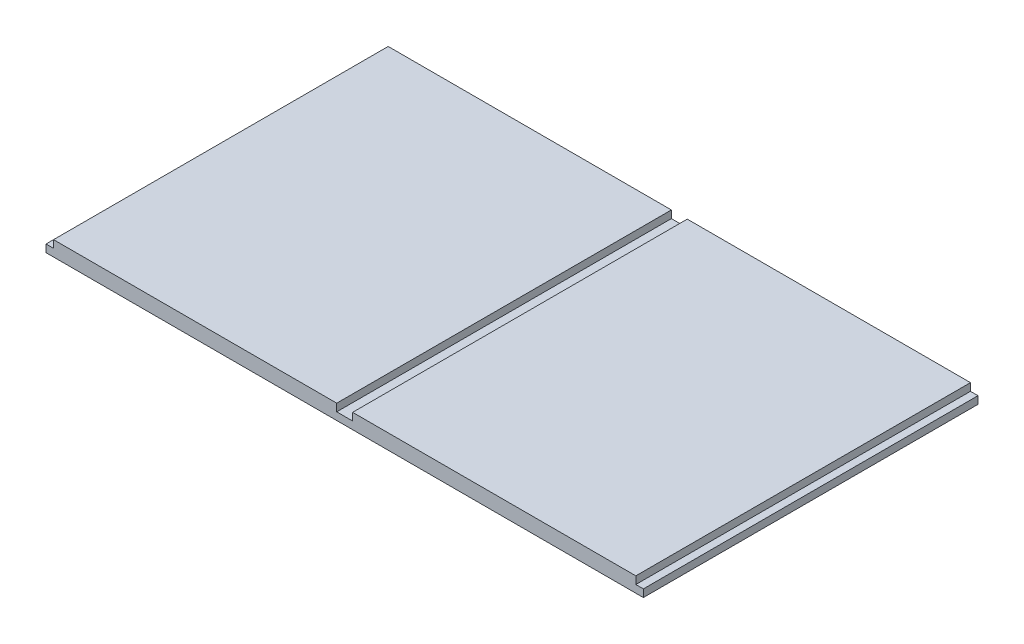
SolidWorks part; units mm, degrees
ref_plane "Front" through (0, 0, 0) normal (0, 0, 1) x (1, 0, 0)
ref_plane "Top" through (0, 0, 0) normal (0, 1, 0) x (1, 0, 0)
ref_plane "Right" through (0, 0, 0) normal (1, 0, 0) x (0, 0, -1)
sketch "Sketch1" plane through (0, 0, 0) normal (0, 1, 0) x (1, 0, 0)
  line L1 (-357, -200) -> (357, -200)
  line L2 (-357, -200) -> (-357, 200)
  line L3 (-357, 200) -> (357, 200)
  line L4 (357, -200) -> (357, 200)
  line L5 (-357, -200) -> (357, 200) construction
  line L6 (-357, 200) -> (357, -200) construction
  point P0 (0, 0)
  dimension "D1" = 714
  dimension "D2" = 400
extrude "Boss-Extrude1" add sketch "Sketch1" along normal blind 18
sketch "Sketch2" plane through (0, 18, 0) normal (0, 1, 0) x (1, 0, 0)
  line L0 (357, 200) -> (-357, 200) construction
  line L1 (357, -200) -> (348, -200)
  line L2 (357, -200) -> (357, 200)
  line L3 (357, 200) -> (348, 200)
  line L4 (348, -200) -> (348, 200)
  line L6 (-357, -200) -> (-348, -200)
  line L7 (-357, -200) -> (-357, 200)
  line L8 (-357, 200) -> (-348, 200)
  line L9 (-348, -200) -> (-348, 200)
  dimension "D1" = 9
  dimension "D2" = 9
extrude "Cut-Extrude1" cut sketch "Sketch2" against normal blind 9
sketch "Sketch3" plane through (0, 18, 0) normal (0, 1, 0) x (1, 0, 0)
  line L0 (348, 200) -> (-348, 200) construction
  line L1 (-9.5, -200) -> (9.5, -200)
  line L2 (-9.5, -200) -> (-9.5, 200)
  line L3 (-9.5, 200) -> (9.5, 200)
  line L4 (9.5, -200) -> (9.5, 200)
  line L5 (-9.5, -200) -> (9.5, 200) construction
  line L6 (-9.5, 200) -> (9.5, -200) construction
  point P0 (0, 0)
  dimension "D1" = 19
extrude "Cut-Extrude2" cut sketch "Sketch3" against normal blind 9
